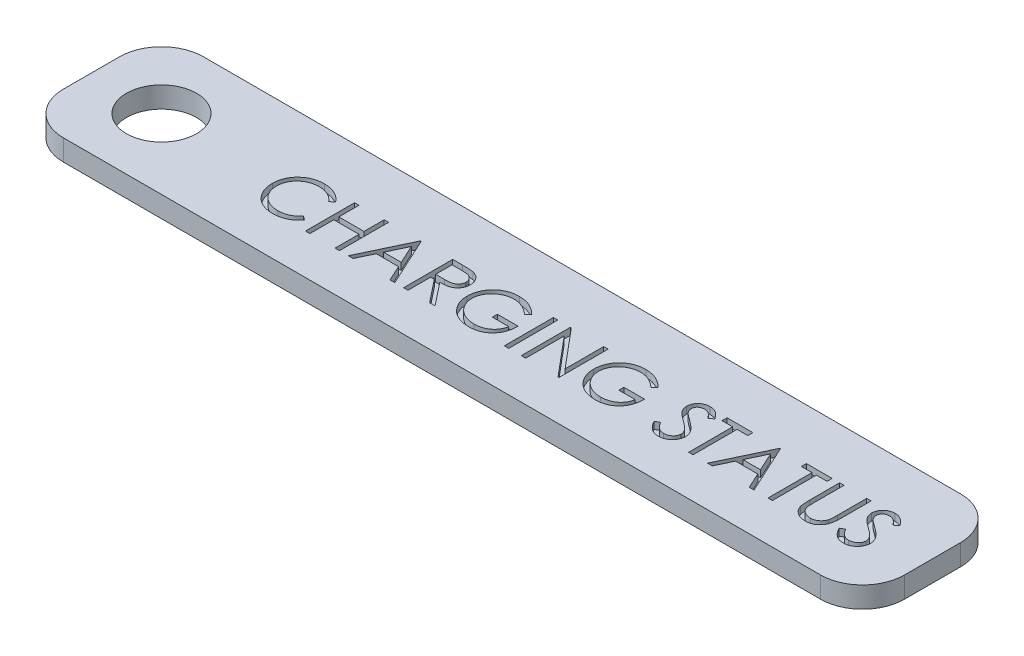
SolidWorks part; units mm, degrees
material "ABS"
ref_plane "Front Plane" through (0, 0, 0) normal (0, 0, 1) x (1, 0, 0)
ref_plane "Top Plane" through (0, 0, 0) normal (0, 1, 0) x (1, 0, 0)
ref_plane "Right Plane" through (0, 0, 0) normal (1, 0, 0) x (0, 0, -1)
sketch "Sketch1" plane through (0, 0, 0) normal (0, 1, 0) x (1, 0, 0)
  line L1 (0, 0) -> (-60, 0)
  line L2 (0, 0) -> (0, -10)
  line L3 (0, -10) -> (-60, -10)
  line L4 (-60, 0) -> (-60, -10)
  dimension "D1" = 10
  dimension "D2" = 60
extrude "Boss-Extrude1" add sketch "Sketch1" along normal blind 1.5
sketch "Sketch4" plane through (0, 1.5, 0) normal (0, 1, 0) x (1, 0, 0)
  line L1 (-60, -10) -> (0, -10) construction
  line L2 (-60, 0) -> (-60, -10) construction
  text T0 "CHARGING STATUS"
  dimension "D1" = 2.875
  dimension "D2" = 13
extrude "Cut-Extrude2" cut sketch "Sketch4" against normal blind 0.5
sketch "Sketch5" plane through (0, 1.5, 0) normal (0, 1, 0) x (1, 0, 0)
  line L0 (0, 0) -> (-60, 0) construction
  line L1 (-60, 0) -> (-60, -10) construction
  circle A0 centre (-55, -5) radius 2.5
  dimension "D1" = 5
  dimension "D3" = 5
  dimension "D2" = 5
extrude "Cut-Extrude3" cut sketch "Sketch5" against normal blind 10.5
fillet "Fillet1" radius 3 4 edges at (0, 0.75, 10) (0, 0.75, 0) (-60, 0.75, 10) (-60, 0.75, 0)
